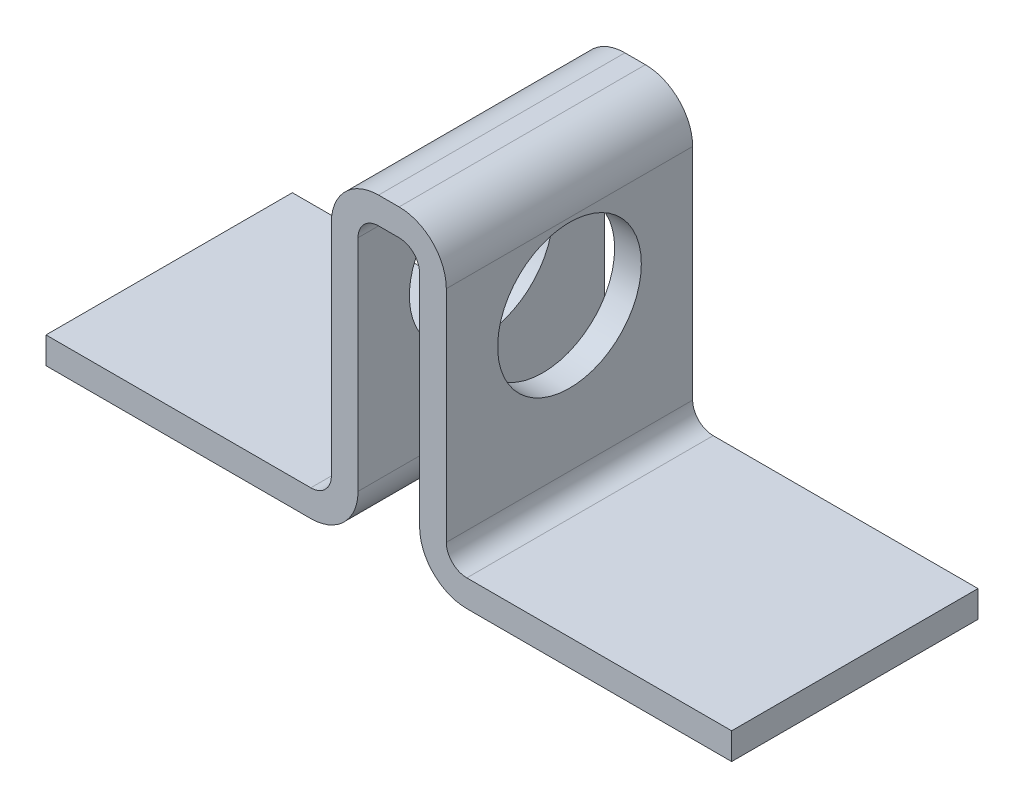
SolidWorks part; units mm, degrees
ref_plane "前视基准面" through (0, 0, 0) normal (0, 0, 1) x (1, 0, 0)
ref_plane "上视基准面" through (0, 0, 0) normal (0, 1, 0) x (1, 0, 0)
ref_plane "右视基准面" through (0, 0, 0) normal (1, 0, 0) x (0, 0, -1)
sketch "草图1" plane through (0, 0, 0) normal (0, 0, 1) x (1, 0, 0)
  line L0 (-16.7, 0) -> (-1.5, 0)
  line L1 (-1.5, 0) -> (-1.5, 14)
  line L2 (0, 0) -> (0, 26.6711) construction
  line L3 (1.5, 0) -> (1.5, 14)
  line L4 (16.7, 0) -> (1.5, 0)
  line L5 (-1.5, 14) -> (1.5, 14)
  dimension "D1" = 33.4
  dimension "D2" = 3
  dimension "D3" = 14
extrude "拉伸-薄壁1" add sketch "草图1" along normal blind 12 thin thin type one direction wall 1.3
hole_wizard "Ø7.0 (7) 直径孔1" positions "草图3" profile "草图2" hole size "Ø7.0" standard "GB" end condition through all
sketch "草图3" plane through (2.8, 0, 0) normal (1, 0, 0) x (0, 0, -1)
  line L0 (-12, 15.3) -> (0, 15.3) construction
  line L1 (0, 2.3) -> (0, 13) construction
  point P0 (-6, 9.3)
  dimension "D1" = 6
  dimension "D2" = 6
sketch "草图2" plane through (2.8, 9.3, 6) normal (0, 1, 0) x (0, 0, -1)
  line L0 (0, 0) -> (0, 19.5)
  line L1 (0, 19.5) -> (3.5, 19.5)
  line L2 (3.5, 19.5) -> (3.5, 0)
  line L5 (3.5, 0) -> (0, 0)
  line L11 (0, -6.35) -> (0, 107.95) construction
  dimension "通孔孔直径" = 7
  dimension "通孔孔深度" = 19.5
